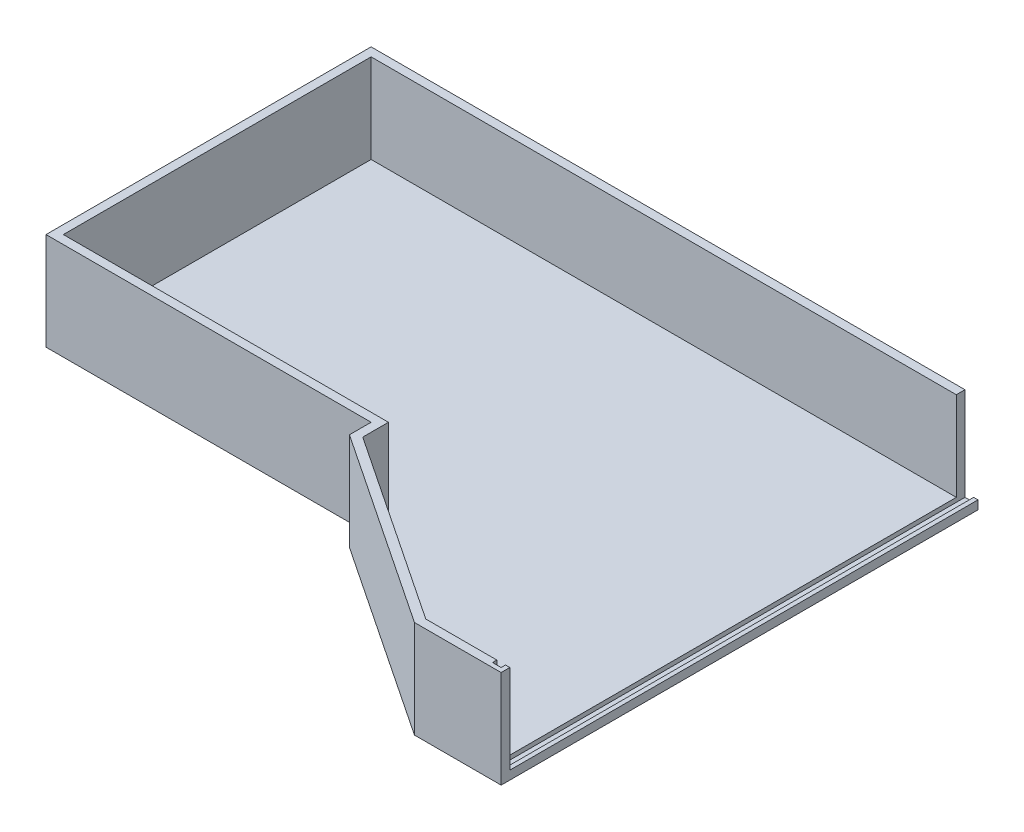
SolidWorks part; units mm, degrees
ref_plane "Front Plane" through (0, 0, 0) normal (0, 0, 1) x (1, 0, 0)
ref_plane "Top Plane" through (0, 0, 0) normal (0, 1, 0) x (1, 0, 0)
ref_plane "Right Plane" through (0, 0, 0) normal (1, 0, 0) x (0, 0, -1)
sketch "Base" plane through (0, 0, 0) normal (0, 1, 0) x (1, 0, 0)
  line L0 (0, 0) -> (140, 0)
  line L1 (140, 0) -> (140, -110)
  line L2 (140, -110) -> (120, -110)
  line L3 (120, -110) -> (75, -80)
  line L4 (75, -80) -> (75, -75)
  line L5 (75, -75) -> (0, -75)
  line L6 (0, -75) -> (0, 0)
  point P8 (0, 0)
  point P9 (-1.8625, -55.6116)
  point P10 (0, -56.3329)
  dimension "D1" = 140
  dimension "D2" = 110
  dimension "D3" = 75
  dimension "D4" = 75
  dimension "D5" = 5
  dimension "D6" = 20
  dimension "D7" = 90
extrude "Boss-Extrude1" add sketch "Base" along normal blind 22.5
sketch "Sketch2" plane through (0, 22.5, 0) normal (0, 1, 0) x (1, 0, 0)
  line L21 (2, -2) -> (2, -73)
  line L22 (2, -73) -> (77, -73)
  line L23 (77, -73) -> (77, -78.9296)
  line L24 (77, -78.9296) -> (120.6056, -108)
  line L25 (120.6056, -108) -> (138, -108)
  line L26 (138, -108) -> (138, -2)
  line L27 (138, -2) -> (2, -2)
  line L28 (2, -2) -> (2, -73)
  line L29 (2, -73) -> (77, -73)
  line L30 (77, -73) -> (77, -78.9296)
  line L31 (77, -78.9296) -> (120.6056, -108)
  line L32 (120.6056, -108) -> (138, -108)
  line L33 (138, -108) -> (138, -2)
  line L34 (138, -2) -> (2, -2)
  dimension "D1" = 2
extrude "Cut-Extrude1" cut sketch "Sketch2" against normal blind 20.5 contours L28 L29 L30 L31 L32 L33 L34
sketch "Sketch3" plane through (138, 0, 0) normal (-1, 0, 0) x (0, 0, 1)
  line L1 (2, 22.5) -> (108, 22.5)
  line L2 (2, 22.5) -> (2, 2)
  line L3 (2, 2) -> (108, 2)
  line L4 (108, 22.5) -> (108, 2)
extrude "Cut-Extrude2" cut sketch "Sketch3" against normal blind 20
sketch "Sketch4" plane through (0, 0, 2) normal (0, 0, 1) x (1, 0, 0)
  line L0 (140, 2) -> (2, 2) construction
  line L1 (140, 22.5) -> (137, 22.5)
  line L2 (140, 22.5) -> (140, 2)
  line L3 (140, 2) -> (137, 2)
  line L4 (137, 22.5) -> (137, 2)
  dimension "D1" = 3
extrude "Cut-Extrude3" cut sketch "Sketch4" against normal blind 20
sketch "Sketch5" plane through (0, 0, 108) normal (0, 0, -1) x (-1, 0, 0)
  line L0 (-140, 2) -> (-139, 2) construction
  line L1 (-120.6056, 2) -> (-140, 2) construction
  line L2 (-120.6056, 22.5) -> (-140, 22.5) construction
  line L3 (-139, 2) -> (-137, 2)
  line L4 (-139, 2) -> (-139, 22.5)
  line L5 (-139, 22.5) -> (-137, 22.5)
  line L6 (-137, 2) -> (-137, 22.5)
  dimension "D1" = 1
  dimension "D2" = 2
extrude "Cut-Extrude4" cut sketch "Sketch5" against normal blind 1
sketch "Sketch7" plane through (0, 2, 0) normal (0, 1, 0) x (1, 0, 0)
  line L1 (139, -109) -> (137, -109)
  line L2 (139, -109) -> (139, 0)
  line L3 (139, 0) -> (137, 0)
  line L4 (137, -109) -> (137, 0)
extrude "Cut-Extrude6" cut sketch "Sketch7" against normal blind 1
